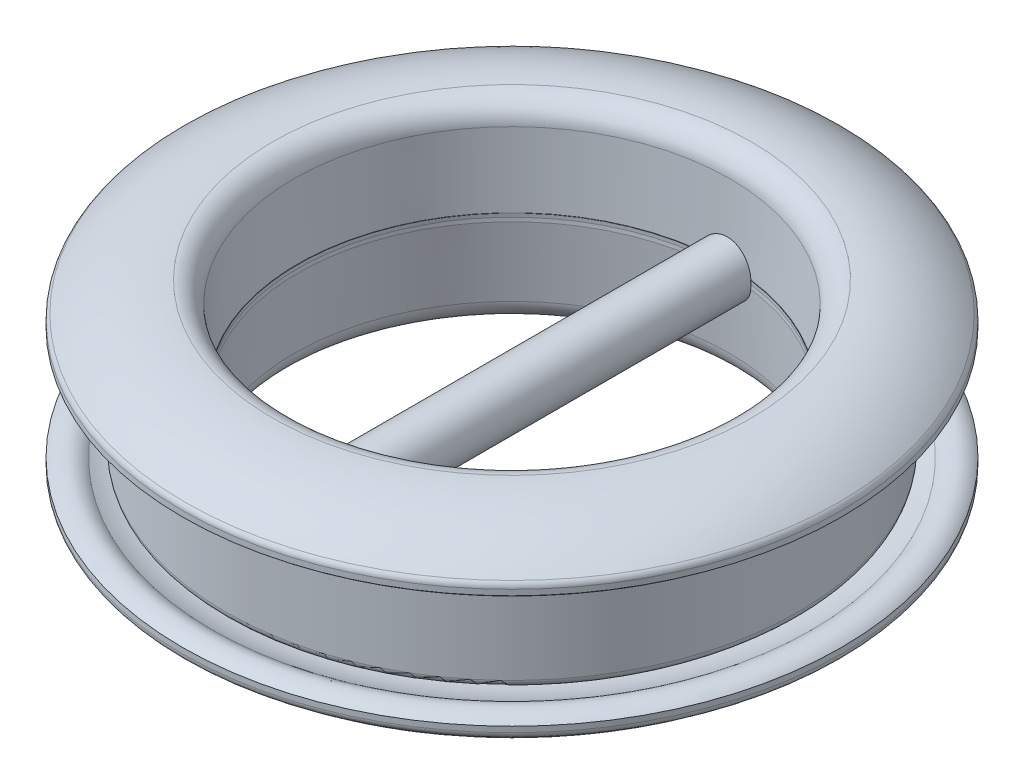
SolidWorks part; units mm, degrees
material "Smooth-Sil™ 940"
ref_plane "Front Plane" through (0, 0, 0) normal (0, 0, 1) x (1, 0, 0)
ref_plane "Top Plane" through (0, 0, 0) normal (0, 1, 0) x (1, 0, 0)
ref_plane "Right Plane" through (0, 0, 0) normal (1, 0, 0) x (0, 0, -1)
ref_plane "Plane2" through (0, -4.572, 0) normal (0, 1, 0) x (1, 0, 0)
ref_plane "Plane4" through (0, -23.622, 0) normal (0, 1, 0) x (1, 0, 0)
ref_plane "Plane3" through (0, -14.097, 0) normal (0, 1, 0) x (1, 0, 0)
sketch "Sketch1" plane through (0, 0, 0) normal (0, 0, 1) x (1, 0, 0)
  line L0 (0, 0) -> (0, 51.7671) construction
  line L1 (36.83, 1.778) -> (36.83, -14.732)
  line L4 (36.83, -14.732) -> (48.26, -14.732)
  line L5 (48.26, -14.732) -> (48.26, -4.826)
  line L6 (48.26, -4.826) -> (43.0459, -4.826)
  line L11 (44.2545, -3.81) -> (39.5655, -3.81) construction
  line L12 (55.5625, -3.048) -> (55.5625, -4.572)
  line L13 (43.0459, -2.794) -> (27.2208, -2.794) construction
  line L14 (30.4487, 2.2962) -> (52.2252, 2.2962) construction
  arc A0 (36.83, 1.778) -> (55.5625, -3.048) centre (41.489, -18.9066) cw
  arc A1 (43.0459, -2.794) -> (43.0459, -4.826) centre (41.91, -3.81) ccw
  arc A2 (55.5625, -4.572) -> (50.4825, -4.572) centre (53.0225, -1.7322) cw
  arc A3 (43.0459, -2.794) -> (50.4825, -4.572) centre (43.0459, -19.2349) cw
  point P23 (41.91, -3.81)
  dimension "D1" = 73.66
  dimension "D5" = 1.524
  dimension "D2" = 2.032
  dimension "D10" = 21.2028
  dimension "D14" = 3.81
  dimension "D15" = 1.524
  dimension "D7" = 1.778
  dimension "D3" = 5.08
  dimension "D4" = 96.52
  dimension "D6" = 5.0902
  dimension "D8" = 83.82
  dimension "D9" = 3.81
  dimension "D11" = 111.125
  dimension "D12" = 14.732
  dimension "D16" = 0.254
revolve "Revolve1" add sketch "Sketch1" angle 360 about L0
draft "Draft1" type of draft neutral plane draft angle 3 neutral plane "Top Plane" faces to draft 1 face at (0, -14.732, -36.83) neutral plane through (0, 0, 0) neutral plane normal (0, 1, 0) parameters "D1"=3
fillet "Fillet3" radius 3.81 1 edges at (0, 1.799, -36.9243)
fillet "Fillet4" radius 1.27 1 edges at (0, -3.048, -55.5625)
fillet "Fillet5" radius 1.27 1 edges at (0, -4.826, -48.26)
mirror "Mirror4" about plane through (0, -14.097, 0) normal (0, 1, 0) of bodies 101
sketch "Sketch2" plane through (0, 0, 0) normal (0, 0, 1) x (1, 0, 0)
  line L0 (61.1187, -14.097) -> (-61.1187, -14.097) construction
  line L1 (-56.5238, -14.097) -> (-54.5176, -14.097)
  line L2 (-56.5238, -14.097) -> (-56.5238, -14.5079)
  line L4 (-54.5176, -14.097) -> (-54.5176, -10.2102)
  line L5 (0, 0) -> (0, -56.0151) construction
  line L6 (-54.5176, -10.2102) -> (-54.5176, -20.3326)
  line L7 (-53.0528, -18.6056) -> (-38.2434, -16.1545)
  line L8 (-36.1217, -13.5156) -> (-36.0579, -14.732)
  line L9 (-48.26, -14.732) -> (48.26, -14.732) construction
  line L10 (-36.0579, -14.732) -> (-38.5979, -14.732)
  line L11 (-38.5979, -14.732) -> (-38.5979, -12.023)
  line L12 (-40.1919, -13.9024) -> (-53.4992, -16.1049)
  line L13 (-56.4949, -19.6371) -> (-56.4949, -14.5079)
  line L15 (-56.4949, -14.5079) -> (-56.5238, -14.5079)
  line L17 (-36.0579, -14.732) -> (36.0579, -14.732) construction
  line L18 (-36.7598, -1.339) -> (-36.0579, -14.732) construction
  line L19 (-36.7598, -1.339) -> (36.7598, -1.339) construction
  arc A0 (-54.5176, -20.3326) -> (-53.0528, -18.6056) centre (-52.767, -20.3326) cw
  arc A1 (-53.4992, -16.1049) -> (-56.4949, -19.6371) centre (-52.9146, -19.6371) ccw
  arc A2 (-38.2434, -16.1545) -> (-36.1217, -13.5156) centre (-38.6582, -13.6486) ccw
  arc A3 (-38.5979, -12.023) -> (-40.1919, -13.9024) centre (-40.5029, -12.023) cw
  dimension "D4" = 2.54
  dimension "D5" = 1.905
  dimension "D1" = 109.0351
  dimension "D2" = 3.8868
  dimension "D3" = 4.7429
  dimension "D6" = 2.54
  dimension "D7" = 2.54
revolve "Revolve2" [suppressed] add sketch "Sketch2" angle 360 about L5
mirror "Mirror5" [suppressed] about plane through (0, -14.097, 0) normal (0, 1, 0)
combine bodies "Combine1" operation type add bodies to combine 105 101
sketch "Sketch4" plane through (0, 0, 0) normal (0, 0, 1) x (1, 0, 0)
  line L0 (61.1187, -14.097) -> (-61.1187, -14.097) construction
  circle A0 centre (0, -14.097) radius 4.4813
extrude "Boss-Extrude1" add sketch "Sketch4" along normal up to next and the other way up to next
